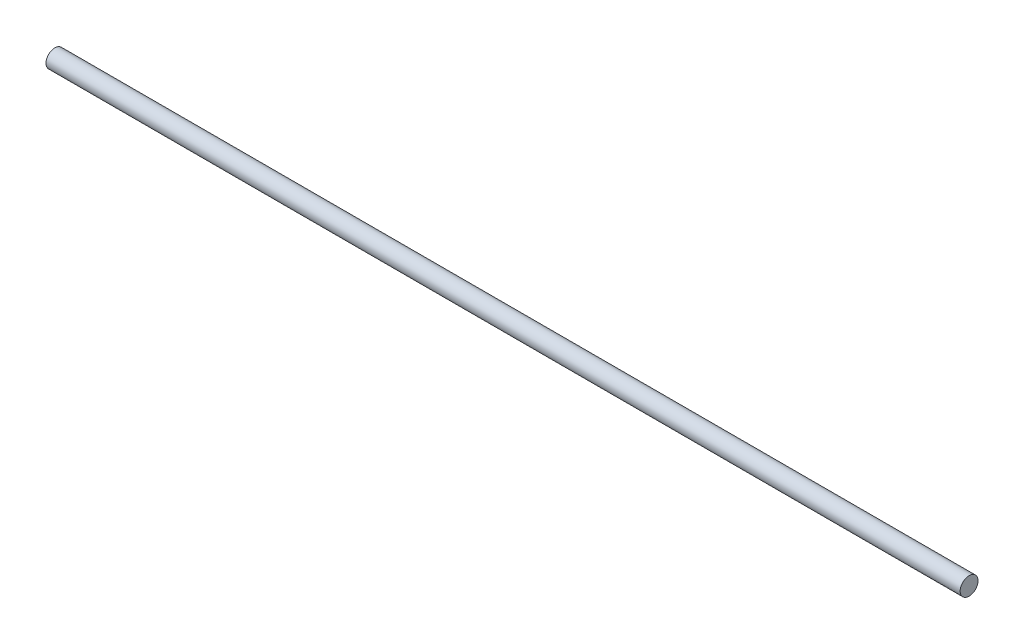
SolidWorks part; units mm, degrees
ref_plane "Front Plane" through (0, 0, 0) normal (0, 0, 1) x (1, 0, 0)
ref_plane "Top Plane" through (0, 0, 0) normal (0, 1, 0) x (1, 0, 0)
ref_plane "Right Plane" through (0, 0, 0) normal (1, 0, 0) x (0, 0, -1)
sketch "Sketch3" plane through (0, 0, 0) normal (1, 0, 0) x (0, 0, -1)
  circle A0 centre (0, 0) radius 4
extrude "Boss-Extrude1" add sketch "Sketch3" along normal blind 410
